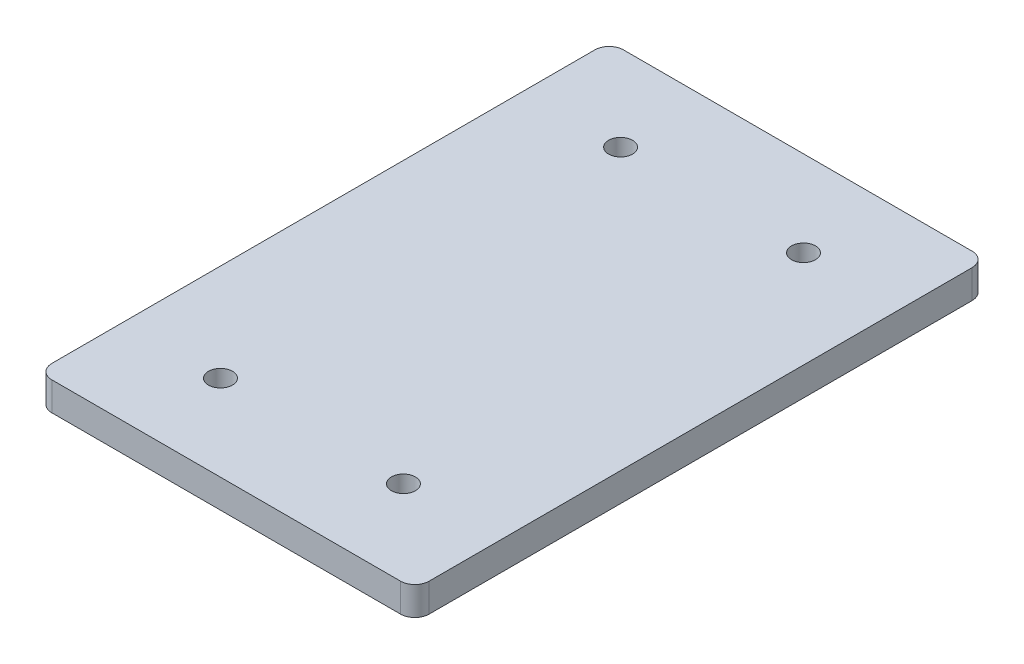
SolidWorks part; units mm, degrees
material "Custom Plastic"
ref_plane "Front Plane" through (0, 0, 0) normal (0, 0, 1) x (1, 0, 0)
ref_plane "Top Plane" through (0, 0, 0) normal (0, 1, 0) x (1, 0, 0)
ref_plane "Right Plane" through (0, 0, 0) normal (1, 0, 0) x (0, 0, -1)
sketch "Sketch1" plane through (0, 0, 0) normal (0, 1, 0) x (1, 0, 0)
  line L1 (33, -50) -> (-33, -50)
  line L2 (33, -50) -> (33, 50)
  line L3 (33, 50) -> (-33, 50)
  line L4 (-33, -50) -> (-33, 50)
  line L5 (33, -50) -> (-33, 50) construction
  line L6 (33, 50) -> (-33, -50) construction
  point P0 (0, 0)
  dimension "D1" = 100
  dimension "D2" = 66
extrude "Boss-Extrude1" add sketch "Sketch1" along normal blind 5
hole_wizard "Ø4.0mm Dowel Hole1" positions "Sketch2" profile "Sketch3" hole size "Ø4.0" standard "ANSI Metric"
sketch "Sketch2" plane through (0, 5, 0) normal (0, 1, 0) x (1, 0, 0)
  line L0 (-16, 35) -> (16, 35) construction
  line L2 (-16, -35) -> (-16, 35) construction
  point P0 (-16, 35)
  point P2 (16, 35)
  point P4 (16, -35)
  point P6 (-16, -35)
  point P17 (0, 35)
  point P23 (-16, 0)
  dimension "D1" = 70
  dimension "D2" = 32
sketch "Sketch3" plane through (-16, 5, -35) normal (1, 0, 0) x (0, 0, 1)
  line L0 (0, 0) -> (0, 3)
  line L1 (0, 3) -> (2.1, 3)
  line L2 (2.1, 3) -> (2.1, 0)
  line L5 (2.1, 0) -> (0, 0)
  line L10 (0, 3) -> (-2.1, 3) construction
  line L11 (0, -6.35) -> (0, 107.95) construction
  dimension "Hole Dia." = 4.2
  dimension "Hole Depth" = 3
  dimension "Drill Angle" = 180
fillet "Fillet1" radius 2.5 4 edges at (-33, 2.5, 50) (33, 2.5, 50) (-33, 2.5, -50) (33, 2.5, -50)
